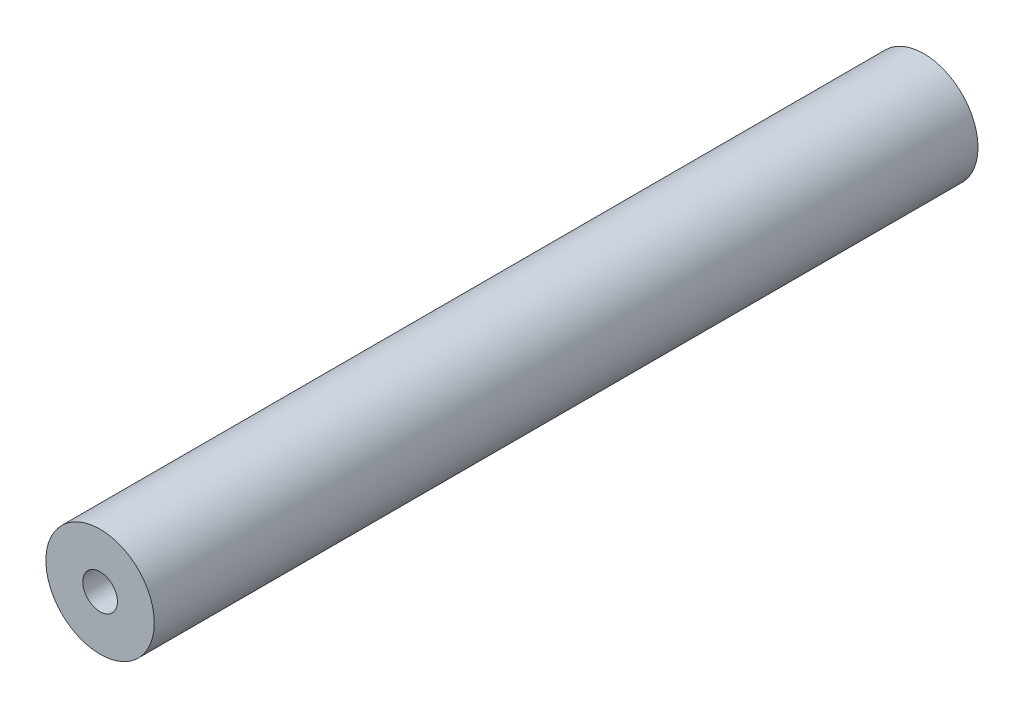
SolidWorks part; units mm, degrees
ref_plane "Front Plane" through (0, 0, 0) normal (0, 0, 1) x (1, 0, 0)
ref_plane "Top Plane" through (0, 0, 0) normal (0, 1, 0) x (1, 0, 0)
ref_plane "Right Plane" through (0, 0, 0) normal (1, 0, 0) x (0, 0, -1)
sketch "Sketch1" plane through (0, 0, 0) normal (0, 0, 1) x (1, 0, 0)
  circle A0 centre (0, 0) radius 12.5
extrude "Boss-Extrude1" add sketch "Sketch1" along normal blind 190
sketch "Sketch2" plane through (0, 0, 0) normal (0, 0, 1) x (1, 0, 0)
  circle A0 centre (0, 0) radius 4
extrude "Cut-Extrude1" cut sketch "Sketch2" along normal blind 395
